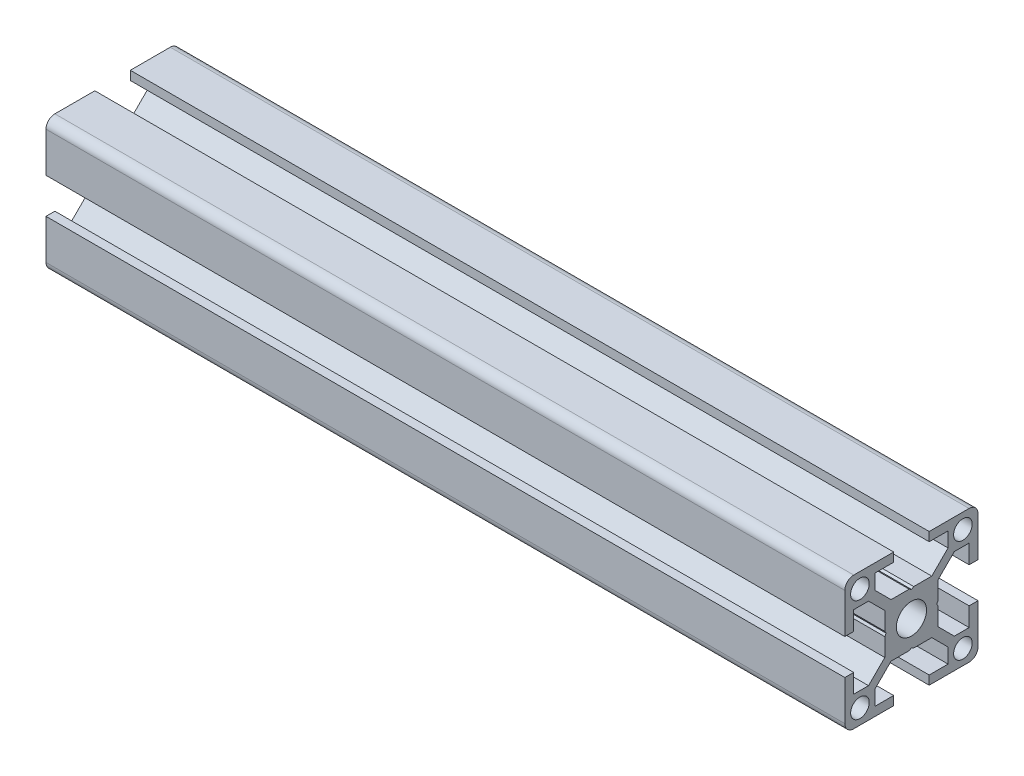
SolidWorks part; units mm, degrees
ref_plane "Front Plane" through (0, 0, 0) normal (0, 0, 1) x (1, 0, 0)
ref_plane "Top Plane" through (0, 0, 0) normal (0, 1, 0) x (1, 0, 0)
ref_plane "Right Plane" through (0, 0, 0) normal (1, 0, 0) x (0, 0, -1)
sketch "Sketch1" plane through (0, 0, 0) normal (0, 0, 1) x (1, 0, 0)
  line L0 (0, 0) -> (180, 0)
  dimension "D1" = 180
other "Ðnh hình 30X30X2(1)"
ref_plane "Plane1" through (0, 0, 0) normal (1, 0, 0) x (0, 1, 0)
sketch "Sketch11" plane through (0, 0, 0) normal (1, 0, 0) x (0, 1, 0)
  line L0 (13, -4) -> (13, -8.25)
  line L1 (13, -8.25) -> (9.6642, -8.25)
  line L2 (9.6642, -8.25) -> (6, -4.5858)
  line L3 (6, -4.5858) -> (6, -0.5196)
  line L4 (6, -0.5196) -> (5.7, 0)
  line L5 (5.7, 0) -> (6, 0.5196)
  line L6 (6, 0.5196) -> (6, 4.5858)
  line L7 (6, 4.5858) -> (9.6642, 8.25)
  line L8 (9.6642, 8.25) -> (13, 8.25)
  line L9 (13, 8.25) -> (13, 4)
  line L10 (13, 4) -> (15, 4)
  line L11 (15, 4) -> (15, 13)
  line L12 (13, 15) -> (4, 15)
  line L13 (4, 15) -> (4, 13)
  line L14 (4, 13) -> (8.25, 13)
  line L15 (8.25, 13) -> (8.25, 9.6642)
  line L16 (8.25, 9.6642) -> (4.5858, 6)
  line L17 (4.5858, 6) -> (0.5196, 6)
  line L18 (0.5196, 6) -> (0, 5.7)
  line L19 (0, 5.7) -> (-0.5196, 6)
  line L20 (-0.5196, 6) -> (-4.5858, 6)
  line L21 (-4.5858, 6) -> (-8.25, 9.6642)
  line L22 (-8.25, 9.6642) -> (-8.25, 13)
  line L23 (-8.25, 13) -> (-4, 13)
  line L24 (-4, 13) -> (-4, 15)
  line L25 (-4, 15) -> (-13, 15)
  line L26 (-15, 13) -> (-15, 4)
  line L27 (-15, 4) -> (-13, 4)
  line L28 (-13, 4) -> (-13, 8.25)
  line L29 (-13, 8.25) -> (-9.6642, 8.25)
  line L30 (-9.6642, 8.25) -> (-6, 4.5858)
  line L31 (-6, 4.5858) -> (-6, 0.5196)
  line L32 (-6, 0.5196) -> (-5.7, 0)
  line L33 (-5.7, 0) -> (-6, -0.5196)
  line L34 (-6, -0.5196) -> (-6, -4.5858)
  line L35 (-6, -4.5858) -> (-9.6642, -8.25)
  line L36 (-9.6642, -8.25) -> (-13, -8.25)
  line L37 (-13, -8.25) -> (-13, -4)
  line L38 (-13, -4) -> (-15, -4)
  line L39 (-15, -4) -> (-15, -13)
  line L40 (-13, -15) -> (-4, -15)
  line L41 (-4, -15) -> (-4, -13)
  line L42 (-4, -13) -> (-8.25, -13)
  line L43 (-8.25, -13) -> (-8.25, -9.6642)
  line L44 (-8.25, -9.6642) -> (-4.5858, -6)
  line L45 (-4.5858, -6) -> (-0.5196, -6)
  line L46 (-0.5196, -6) -> (0, -5.7)
  line L47 (0, -5.7) -> (0.5196, -6)
  line L48 (0.5196, -6) -> (4.5858, -6)
  line L49 (4.5858, -6) -> (8.25, -9.6642)
  line L50 (8.25, -9.6642) -> (8.25, -13)
  line L51 (8.25, -13) -> (4, -13)
  line L52 (4, -13) -> (4, -15)
  line L53 (4, -15) -> (13, -15)
  line L54 (15, -13) -> (15, -4)
  line L55 (15, -4) -> (13, -4)
  arc A0 (15, 13) -> (13, 15) centre (13, 13) ccw
  arc A1 (-13, 15) -> (-15, 13) centre (-13, 13) ccw
  arc A2 (-15, -13) -> (-13, -15) centre (-13, -13) ccw
  arc A3 (13, -15) -> (15, -13) centre (13, -13) ccw
  circle A4 centre (0, 0) radius 3.4
  circle A5 centre (11.6, -11.6) radius 2.1
  circle A6 centre (11.6, 11.6) radius 2.1
  circle A7 centre (-11.6, 11.6) radius 2.1
  circle A8 centre (-11.6, -11.6) radius 2.1
  point P74 (0, 0)
